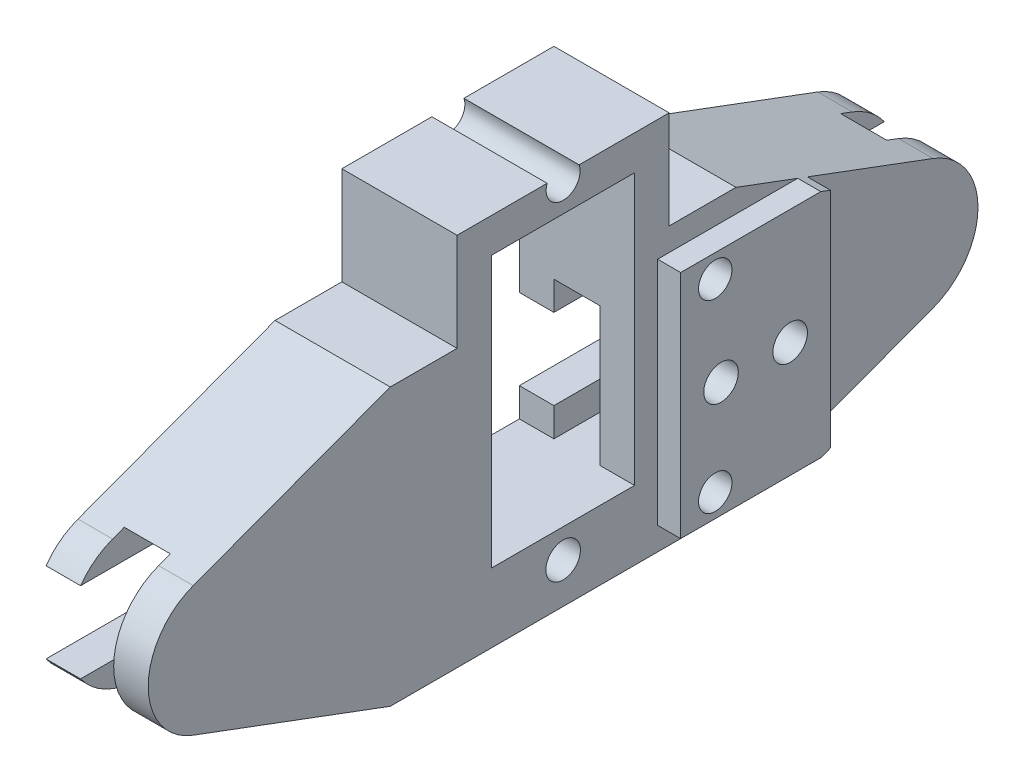
SolidWorks part; units mm, degrees
ref_plane "前视基准面" through (0, 0, 0) normal (0, 0, 1) x (1, 0, 0)
ref_plane "上视基准面" through (0, 0, 0) normal (0, 1, 0) x (1, 0, 0)
ref_plane "右视基准面" through (0, 0, 0) normal (1, 0, 0) x (0, 0, -1)
other "Configuration Table"
sketch "草图1" plane through (0, 0, 0) normal (1, 0, 0) x (0, 0, -1)
  line L0 (-32.0972, 5.6215) -> (-15, 12)
  line L1 (15, -12) -> (-15, -12)
  line L3 (15, 12) -> (-15, 12)
  line L7 (32.0972, 5.6215) -> (15, 12)
  line L8 (32.0972, -5.6215) -> (15, -12)
  line L9 (-32.0972, -5.6215) -> (-15, -12)
  arc A0 (-32.0972, 5.6215) -> (-32.0972, -5.6215) centre (-30, 0) ccw
  arc A1 (32.0972, -5.6215) -> (32.0972, 5.6215) centre (30, 0) ccw
  point P4 (0, 0)
  dimension "D1" = 30
  dimension "D3" = 12
  dimension "D4" = 12
  dimension "D7" = 12
  dimension "D10" = 17.0972
  dimension "D2" = 30
  dimension "D5" = 30
  dimension "D6" = 24
  dimension "D8" = 12
  dimension "D9" = 5.6215
  dimension "D11" = 17.0972
  dimension "D12" = 17.0972
extrude "凸台-拉伸1" add sketch "草图1" along normal blind 10
ref_plane "基准面1" through (0, 0, 36) normal (0, 0, 1) x (1, 0, 0)
sketch "草图2" plane through (0, 0, 36) normal (0, 0, 1) x (1, 0, 0)
  line L0 (-8.5518, 0) -> (17.9633, 0) construction
  line L1 (3, -3.5) -> (3, -6)
  line L2 (7, 6) -> (7, -6)
  line L3 (10, -5.6215) -> (10, 5.6215) construction
  line L4 (3, 6) -> (7, 6)
  line L5 (3, -6) -> (7, -6)
  line L6 (0, -3.5) -> (3, -3.5)
  line L7 (0, 3.5) -> (3.0506, 3.5)
  line L8 (3, 6) -> (3, 3.5)
  line L9 (0, 5.6215) -> (0, -5.6215) construction
  line L10 (0, 3.5) -> (0, -3.5)
  dimension "D1" = 3
  dimension "D2" = 6
  dimension "D3" = 6
  dimension "D4" = 3
  dimension "D5" = 2.5
  dimension "D6" = 2.5
extrude "切除-拉伸1" cut sketch "草图2" against normal through all both and the other way through all
sketch "草图3" plane through (10, 0, 0) normal (1, 0, 0) x (0, 0, -1)
  line L0 (-9.2, 20.5) -> (9.2, 20.5)
  line L5 (-6.2, -6) -> (6.2, -6)
  line L6 (-6.2, -6) -> (-6.2, 17.5)
  line L7 (-6.2, 17.5) -> (6.2, 17.5)
  line L8 (6.2, -6) -> (6.2, 17.5)
  line L9 (9.2, -9) -> (9.2, 20.5)
  line L10 (-9.2, -9) -> (9.2, -9)
  line L11 (-9.2, -9) -> (-9.2, 20.5)
  line L12 (-9.2, 12) -> (9.7138, 12)
  line L13 (15, 12) -> (-15, 12) construction
  point P0 (0, 0)
  line M3 (15, 12) -> (-15, 12)
  dimension "D1" = 6
  dimension "D2" = 6.2
  dimension "D3" = 6.2
  dimension "D4" = 23.5
  dimension "D5" = 3
extrude "切除-拉伸4" cut sketch "草图3" against normal blind 10 contours L5 L8 L6 M3
sketch "草图4" plane through (10, 0, 0) normal (1, 0, 0) x (0, 0, -1)
  line L0 (-6.2, 17.5) -> (6.2, 17.5)
  line L1 (-6.2, -6) -> (6.2, -6) construction
  line L2 (-6.2, 12) -> (-6.2, 17.5)
  line L3 (6.2, 12) -> (6.2, 17.5)
  line L4 (15, 12) -> (6.2, 12) construction
  line L5 (-6.2, 12) -> (-15, 12) construction
  line L6 (9.2, 12) -> (6.2, 12)
  line L7 (-6.2, 12) -> (-9.2, 12)
  line L8 (-9.2, 15) -> (-9.2, 20.5) construction
  line L9 (-9.2, 12) -> (-9.2, 20.5)
  line L10 (-9.2, 20.5) -> (9.2, 20.5)
  line L11 (9.2, 12) -> (9.2, 20.5)
  line L12 (9.2, 15) -> (9.2, 20.5) construction
  line L13 (-9.2, 15) -> (-15, 15) construction
  line L14 (15, 15) -> (9.2, 15) construction
  line L15 (15, 12) -> (6.2, 12) construction
  line L16 (-6.2, 12) -> (-15, 12) construction
  dimension "D1" = 23.5
  dimension "D2" = 3
extrude "凸台-拉伸3" add sketch "草图4" against normal blind 10
sketch "草图5" plane through (10, 0, 0) normal (1, 0, 0) x (0, 0, -1)
  line L0 (-6.2, -6) -> (6.2, -6) construction
  line L1 (-6.2, 17.5) -> (6.2, 17.5) construction
  circle A0 centre (0, -8.5) radius 1.4
  circle A1 centre (0, 20) radius 1.4
  dimension "D1" = 2.8
  dimension "D3" = 8.5
  dimension "D4" = 2.8
  dimension "D6" = 20
  dimension "D2" = 2.5
  dimension "D5" = 2.5
extrude "切除-拉伸5" cut sketch "草图5" against normal blind 10
sketch "草图6" plane through (10, 0, 0) normal (1, 0, 0) x (0, 0, -1)
  circle A0 centre (0, 20) radius 1.475
  circle A1 centre (0, -8.5) radius 1.5
  dimension "D1" = 2.95
  dimension "D2" = 3
extrude "切除-拉伸6" cut sketch "草图6" against normal blind 10
sketch "草图7" plane through (10, 0, 0) normal (1, 0, 0) x (0, 0, -1)
  line L0 (15, 12) -> (9.2, 12) construction
  line L1 (8.2, -10) -> (20.3609, -10)
  line L2 (8.2, -10) -> (8.2, 10)
  line L3 (8.2, 10) -> (20.3609, 10)
  line L4 (21.2, -9.687) -> (21.2, 9.687)
  line L5 (-15, -12) -> (15, -12) construction
  line L6 (6.2, -6) -> (6.2, 17.5) construction
  line L7 (32.0972, 5.6215) -> (15, 12) construction
  line L8 (15, -12) -> (32.0972, -5.6215) construction
  line L9 (21.2, 9.687) -> (20.3609, 10)
  line L10 (20.3609, -10) -> (21.2, -9.687)
  dimension "D1" = 2
  dimension "D2" = 2
  dimension "D3" = 2
  dimension "D4" = 15
extrude "凸台-拉伸4" add sketch "草图7" along normal blind 2
sketch "草图8" plane through (12, 0, 0) normal (1, 0, 0) x (0, 0, -1)
  line L0 (8.2, 10) -> (8.2, -10) construction
  line L1 (8.2, -10) -> (20.3609, -10) construction
  circle A0 centre (11.7, 0) radius 1.5
  circle A1 centre (17.7, 0) radius 1.5
  dimension "D1" = 3
  dimension "D2" = 3
  dimension "D3" = 3.5
  dimension "D4" = 6
  dimension "D5" = 10
  dimension "D6" = 10
extrude "切除-拉伸8" cut sketch "草图8" against normal through all
sketch "草图9" plane through (7, 0, 0) normal (-1, 0, 0) x (0, 0, 1)
  circle A0 centre (-17.7, 0) radius 2.75
  circle A1 centre (-11.7, 0) radius 2.75
  dimension "D1" = 5.5
extrude "切除-拉伸9" cut sketch "草图9" against normal blind 2
sketch "草图10" plane through (12, 0, 0) normal (1, 0, 0) x (0, 0, -1)
  line L0 (20.3609, 10) -> (8.2, 10) construction
  line L1 (8.2, -10) -> (20.3609, -10) construction
  line L2 (8.2, 10) -> (8.2, -10) construction
  circle A0 centre (11.2, 8) radius 1.45
  circle A1 centre (11.2, -8) radius 1.45
  point P13 (0, 0)
  dimension "D1" = 2
  dimension "D4" = 2.9
  dimension "D2" = 2
  dimension "D3" = 3
extrude "切除-拉伸10" cut sketch "草图10" against normal blind 5
